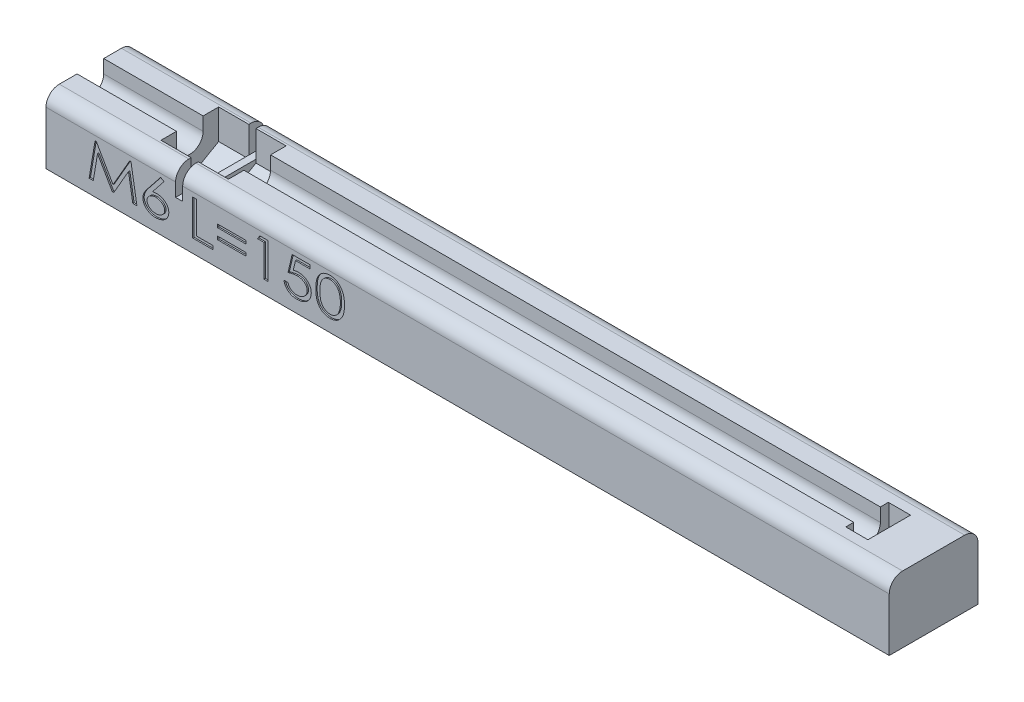
SolidWorks part; units mm, degrees
ref_plane "Front Plane" through (0, 0, 0) normal (0, 0, 1) x (1, 0, 0)
ref_plane "Top Plane" through (0, 0, 0) normal (0, 1, 0) x (1, 0, 0)
ref_plane "Right Plane" through (0, 0, 0) normal (1, 0, 0) x (0, 0, -1)
sketch "Sketch1" plane through (0, 0, 0) normal (0, 1, 0) x (1, 0, 0)
  line L1 (90, 10) -> (-90, 10)
  line L2 (90, 10) -> (90, -10)
  line L3 (90, -10) -> (-90, -10)
  line L4 (-90, 10) -> (-90, -10)
  line L5 (90, 10) -> (-90, -10) construction
  line L6 (90, -10) -> (-90, 10) construction
  point P0 (0, 0)
  dimension "D1" = 180
  dimension "D2" = 20
extrude "Boss-Extrude1" add sketch "Sketch1" along normal blind 15
sketch "Sketch2" plane through (0, 0, 0) normal (1, 0, 0) x (0, 0, -1)
  line L0 (-10, 15) -> (10, 15) construction
  line L1 (-3, 15) -> (-3, 12)
  line L2 (3, 12) -> (3, 15)
  line L3 (-3, 15) -> (3, 15)
  arc A0 (-3, 12) -> (3, 12) centre (0, 12) ccw
  dimension "D1" = 6
  dimension "D2" = 3
extrude "Cut-Extrude1" cut sketch "Sketch2" against normal up to next and the other way up to next
sketch "Sketch4" plane through (90, 0, 0) normal (1, 0, 0) x (0, 0, -1)
  line L1 (-3, 15) -> (3, 15)
  line L7 (-3, 12) -> (-3, 15)
  line L8 (-3, 15) -> (-10, 15)
  line L9 (-10, 15) -> (-10, 0)
  line L10 (-10, 0) -> (10, 0)
  line L11 (10, 0) -> (10, 15)
  line L12 (10, 15) -> (3, 15)
  line L13 (3, 15) -> (3, 12)
  line L15 (-3, 15) -> (-10, 15)
  line L16 (-10, 15) -> (-10, 0)
  line L17 (-10, 0) -> (10, 0)
  line L18 (10, 0) -> (10, 15)
  line L19 (10, 15) -> (3, 15)
  arc A1 (-3, 12) -> (3, 12) centre (0, 12) ccw
  dimension "D1" = 0
extrude "Boss-Extrude2" add sketch "Sketch4" along normal blind 10
ref_plane "Plane1" through (90, 0, 0) normal (-1, 0, 0) x (0, 0, 1)
sketch "Sketch5" plane through (90, 0, 0) normal (-1, 0, 0) x (0, 0, 1)
  line L1 (0, 6.2265) -> (5, 9.1132)
  line L2 (5, 9.1132) -> (5, 14.8868)
  line L3 (5, 14.8868) -> (0, 17.7735)
  line L4 (0, 17.7735) -> (-5, 14.8868)
  line L5 (-5, 14.8868) -> (-5, 9.1132)
  line L6 (-5, 9.1132) -> (0, 6.2265)
  circle A0 centre (0, 12) radius 5 construction
  dimension "D1" = 10
extrude "Cut-Extrude2" cut sketch "Sketch5" along normal blind 5
sketch "Sketch6" plane through (0, 0, 0) normal (0, 0, 1) x (1, 0, 0)
  line L0 (-60, 58.8823) -> (-60, -36.514) construction
  line L1 (90, 4.8254) -> (90, -4.8254) construction
  dimension "D1" = 150
ref_plane "cut mid" through (-60, 0, 0) normal (-1, 0, 0) x (0, 0, 1)
sketch "Sketch8" plane through (0, 0, 10) normal (0, 0, 1) x (1, 0, 0)
  line L0 (-81, 3) -> (19, 3) construction
  line L2 (-90, 0) -> (100, 0) construction
  text T0 "M6 L=150" font "Century Gothic" height 8
  dimension "D1" = 3
  dimension "D2" = 100
  dimension "D3" = 9
extrude "Cut-Extrude3" cut sketch "Sketch8" against normal blind 0.3
ref_plane "cut1" through (-60.8, 0, 0) normal (-1, 0, 0) x (0, 0, 1)
sketch "Sketch9" plane through (-60.8, 0, 0) normal (-1, 0, 0) x (0, 0, 1)
  line L0 (-19.0805, 12) -> (18.3323, 12) construction
  line L1 (0, 4.4944) -> (6.5, 8.2472)
  line L2 (6.5, 8.2472) -> (6.5, 15.7528)
  line L3 (6.5, 15.7528) -> (0, 19.5056)
  line L4 (0, 19.5056) -> (-6.5, 15.7528)
  line L5 (-6.5, 15.7528) -> (-6.5, 8.2472)
  line L6 (-6.5, 8.2472) -> (0, 4.4944)
  circle A0 centre (0, 12) radius 6.5 construction
  dimension "D1" = 13
extrude "Cut-Extrude4" cut sketch "Sketch9" along normal blind 6.8
mirror "Mirror1" about plane through (-60, 0, 0) normal (-1, 0, 0) of "Cut-Extrude4"
sketch "Sketch10" plane through (0, 15, 0) normal (0, 1, 0) x (1, 0, 0)
  line L0 (100, 10) -> (-90, 10) construction
  line L1 (-60.8, 10) -> (-59.2, 10)
  line L2 (-60.8, 10) -> (-60.8, -10)
  line L3 (-60.8, -10) -> (-59.2, -10)
  line L4 (-59.2, 10) -> (-59.2, -10)
  line L5 (-90, -10) -> (100, -10) construction
  line L6 (-59.2, -3) -> (-59.2, -6.5) construction
extrude "Cut-Extrude5" cut sketch "Sketch10" against normal blind 6
fillet "Fillet1" radius 3 4 edges at (-75.4, 15, 10) (-75.4, 15, -10) (20.4, 15, -10) (20.4, 15, 10)
